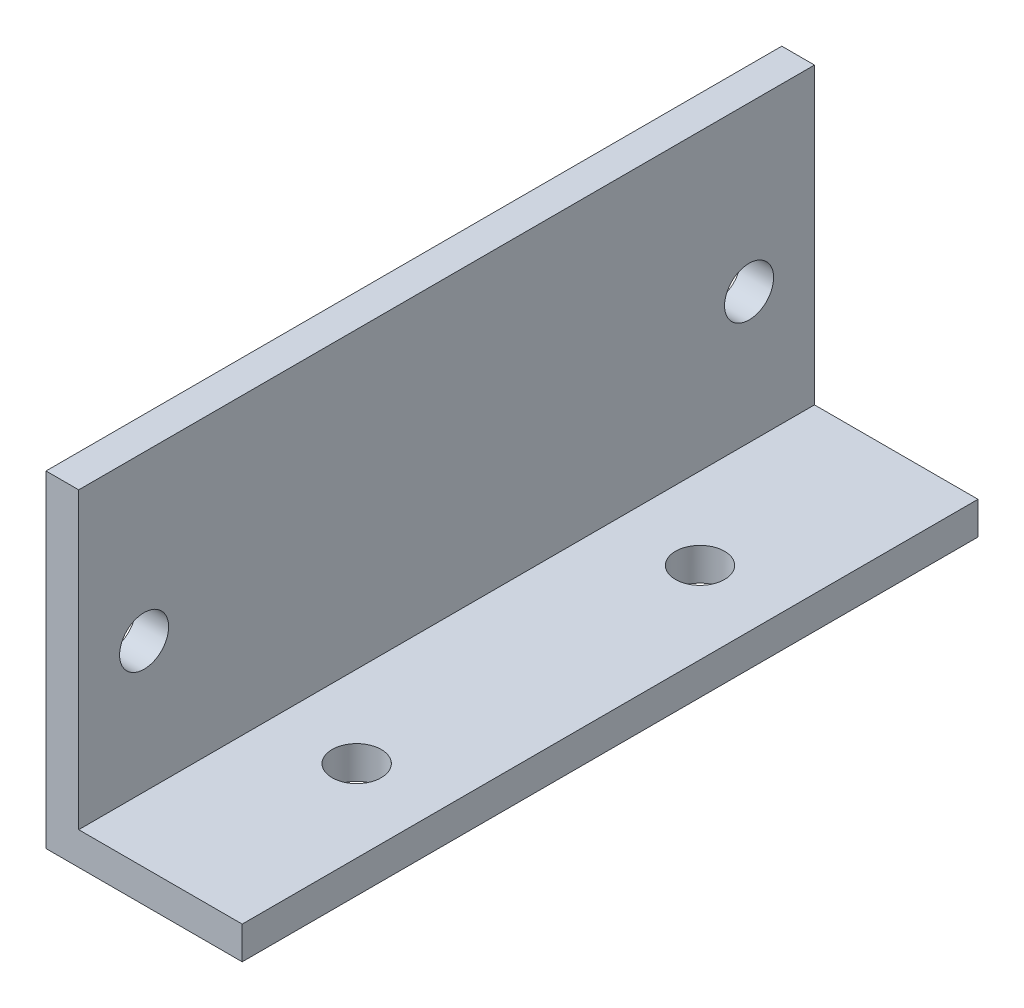
SolidWorks part; units mm, degrees
ref_plane "前视基准面" through (0, 0, 0) normal (0, 0, 1) x (1, 0, 0)
ref_plane "上视基准面" through (0, 0, 0) normal (0, 1, 0) x (1, 0, 0)
ref_plane "右视基准面" through (0, 0, 0) normal (1, 0, 0) x (0, 0, -1)
sketch "草图1" plane through (0, 0, 0) normal (0, 0, 1) x (1, 0, 0)
  line L0 (-8.16, 16.2) -> (-6.16, 16.2)
  line L1 (-6.16, 16.2) -> (-6.16, -1.8)
  line L2 (-6.16, -1.8) -> (3.84, -1.8)
  line L3 (3.84, -1.8) -> (3.84, -3.8)
  line L4 (3.84, -3.8) -> (-8.16, -3.8)
  line L5 (-8.16, -3.8) -> (-8.16, 16.2)
  dimension "D1" = 2
  dimension "D2" = 2
  dimension "D3" = 10
  dimension "D4" = 20
extrude "凸台-拉伸1" add sketch "草图1" along normal blind 45
sketch "草图2" plane through (-8.16, 0, 0) normal (-1, 0, 0) x (0, 0, 1)
  line L0 (-8.9977, 6.2) -> (52.002, 6.2) construction
  line L1 (22.5, 16.2) -> (22.5, -3.8) construction
  line L2 (45, 16.2) -> (0, 16.2) construction
  line L3 (45, -3.8) -> (0, -3.8) construction
  circle A0 centre (4, 6.2) radius 1.5
  circle A1 centre (41, 6.2) radius 1.5
  dimension "D1" = 37
  dimension "D2" = 10
extrude "切除-拉伸1" cut sketch "草图2" against normal through all
sketch "草图3" plane through (0, -3.8, 0) normal (0, -1, 0) x (1, 0, 0)
  line L0 (-8.16, 22.5) -> (3.84, 22.5) construction
  line L1 (-8.16, 45) -> (-8.16, 0) construction
  line L2 (3.84, 45) -> (3.84, 0) construction
  line L3 (-8.16, 45) -> (3.84, 45) construction
  line L4 (-1.16, 45) -> (-1.16, 0) construction
  line L5 (-8.16, 0) -> (3.84, 0) construction
  circle A0 centre (-1.16, 33) radius 1.5
  circle A1 centre (-1.16, 12) radius 1.5
  dimension "D1" = 3
  dimension "D2" = 7
  dimension "D3" = 21
extrude "切除-拉伸2" cut sketch "草图3" against normal through all
